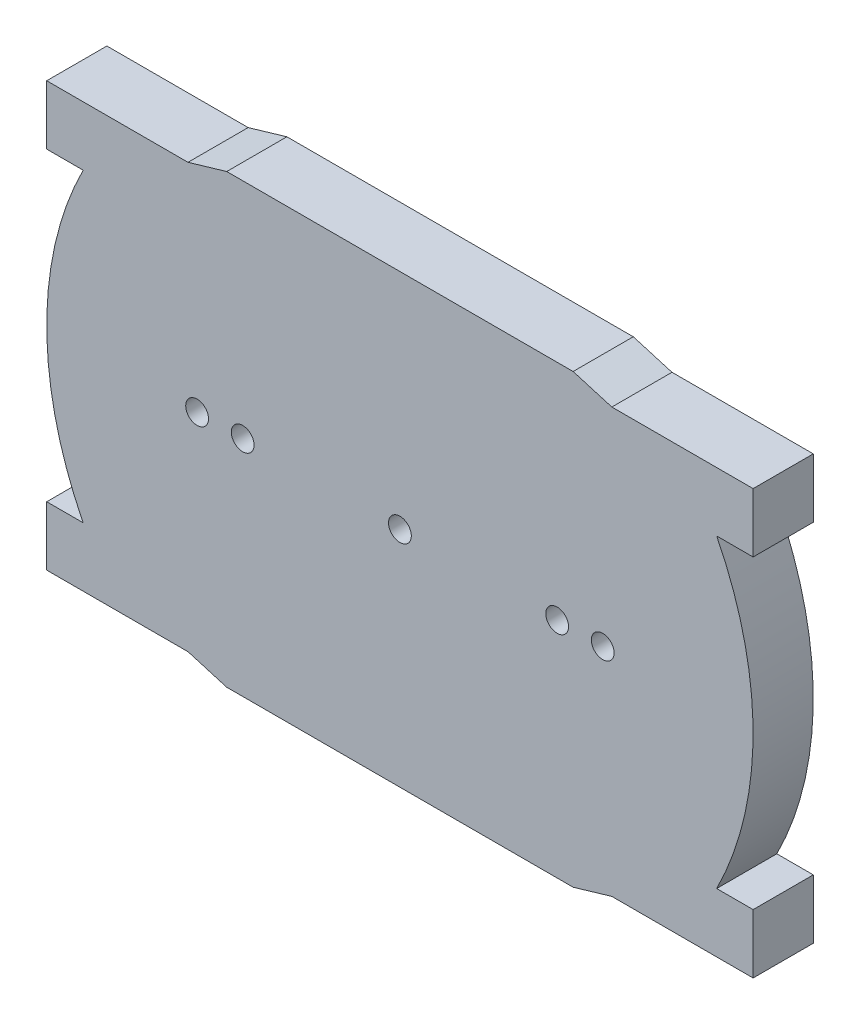
SolidWorks part; units mm, degrees
ref_plane "前视基准面" through (0, 0, 0) normal (0, 0, 1) x (1, 0, 0)
ref_plane "上视基准面" through (0, 0, 0) normal (0, 1, 0) x (1, 0, 0)
ref_plane "右视基准面" through (0, 0, 0) normal (1, 0, 0) x (0, 0, -1)
sketch "草图1" plane through (0, 0, 0) normal (0, 0, 1) x (1, 0, 0)
  line L0 (0, 72.4752) -> (0, -78.8585) construction
  line L1 (-77.5, 49) -> (77.5, 49)
  line L2 (-77.5, 49) -> (-77.5, -49)
  line L3 (-77.5, -49) -> (77.5, -49)
  line L4 (77.5, 49) -> (77.5, -49)
  line L5 (-109.7664, 0) -> (128.4587, 0) construction
  dimension "D1" = 155
  dimension "D2" = 98
extrude "凸台-拉伸1" add sketch "草图1" along normal blind 13.2
sketch "草图2" plane through (0, 0, 13.2) normal (0, 0, 1) x (1, 0, 0)
  line L0 (0, 55.2134) -> (0, -56.7825) construction
  line L1 (-93.0684, 0) -> (90.1263, 0) construction
  line L2 (-38, 49) -> (-46.5, 46.5)
  line L4 (77.5, 49) -> (-77.5, 49) construction
  line L5 (-46.5, 46.5) -> (-77.5, 46.5)
  line L7 (-77.5, 49) -> (-77.5, -49) construction
  line L8 (-77.5, 46.5) -> (-77.5, 49)
  line L9 (-77.5, 49) -> (-38, 49)
  line L10 (77.5, 49) -> (38, 49)
  line L11 (77.5, 46.5) -> (77.5, 49)
  line L12 (46.5, 46.5) -> (77.5, 46.5)
  line L13 (38, 49) -> (46.5, 46.5)
  line L14 (38, -49) -> (46.5, -46.5)
  line L15 (46.5, -46.5) -> (77.5, -46.5)
  line L16 (77.5, -46.5) -> (77.5, -49)
  line L17 (77.5, -49) -> (38, -49)
  line L18 (-77.5, -49) -> (-38, -49)
  line L19 (-77.5, -46.5) -> (-77.5, -49)
  line L20 (-46.5, -46.5) -> (-77.5, -46.5)
  line L21 (-38, -49) -> (-46.5, -46.5)
  dimension "D1" = 76
  dimension "D2" = 93
  dimension "D3" = 31
extrude "切除-拉伸1" cut sketch "草图2" against normal through all
sketch "草图3" plane through (0, 0, 13.2) normal (0, 0, 1) x (1, 0, 0)
  line L0 (-113.5829, 0) -> (96.2926, 0) construction
  line L1 (0, 67.6043) -> (0, -58.321) construction
  line L2 (-77.5, -33.5) -> (-69.5, -33.5)
  line L3 (-77.5, 33.5) -> (-69.5, 33.5)
  line L4 (-77.5, 46.5) -> (-77.5, -46.5) construction
  line L5 (-77.5, -33.5) -> (-77.5, 33.5)
  line L6 (-77.5, 46.5) -> (-46.5, 46.5) construction
  line L7 (77.5, -33.5) -> (77.5, 33.5)
  line L8 (77.5, 33.5) -> (69.5, 33.5)
  line L9 (77.5, -33.5) -> (69.5, -33.5)
  line L10 (-77.49, 8.2674) -> (-77.49, -11.0205) construction
  arc A0 (-69.5, 33.5) -> (-69.5, -33.5) centre (-3.2666, 0) ccw
  arc A1 (69.5, 33.5) -> (69.5, -33.5) centre (3.2666, 0) cw
  point P15 (-77.5, 0)
  point P18 (77.5, 0)
  dimension "D1" = 13
  dimension "D2" = 8
  dimension "D3" = 0.01
extrude "切除-拉伸2" cut sketch "草图3" against normal through all
sketch "草图4" plane through (0, 0, 0) normal (0, 0, -1) x (-1, 0, 0)
  line L0 (-96.4027, 0) -> (94.6375, 0) construction
  line L1 (0, 51.8153) -> (0, -53.8033) construction
  circle A0 centre (-44.5, 0) radius 2.5
  circle A1 centre (-34.5, 0) radius 2.5
  circle A2 centre (0, 0) radius 2.5
  circle A3 centre (34.5, 0) radius 2.5
  circle A4 centre (44.5, 0) radius 2.5
  dimension "D1" = 5
  dimension "D2" = 5
  dimension "D3" = 5
  dimension "D4" = 69
  dimension "D5" = 89
extrude "切除-拉伸3" cut sketch "草图4" against normal blind 13.2
